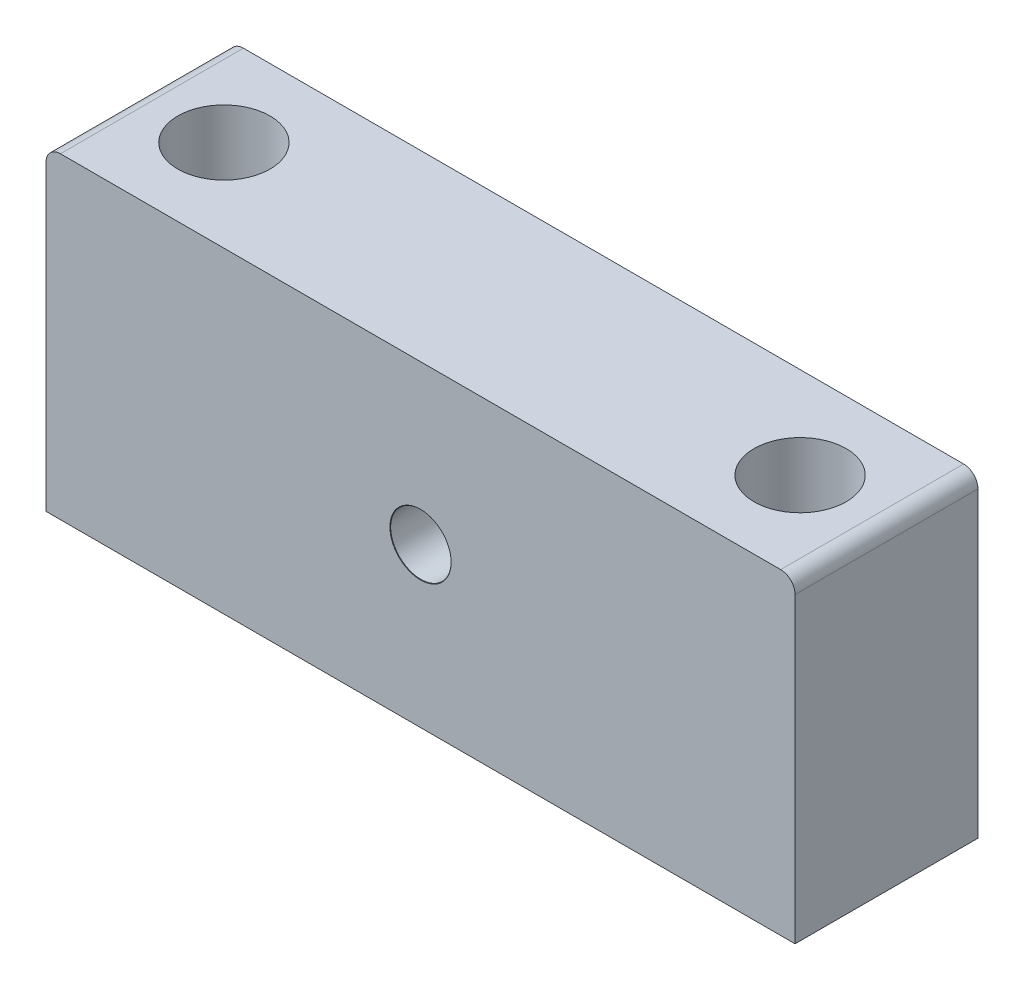
SolidWorks part; units mm, degrees
material "6061 Alloy"
ref_plane "Front Plane" through (0, 0, 0) normal (0, 0, 1) x (1, 0, 0)
ref_plane "Top Plane" through (0, 0, 0) normal (0, 1, 0) x (1, 0, 0)
ref_plane "Right Plane" through (0, 0, 0) normal (1, 0, 0) x (0, 0, -1)
sketch "Sketch1" plane through (0, 0, 0) normal (0, 0, 1) x (1, 0, 0)
  line L0 (-26, 0) -> (26, 0)
  line L1 (26, 0) -> (26, 6)
  line L2 (26, 6) -> (11, 6) construction
  line L3 (-26, 0) -> (-26, 6)
  line L4 (-26, 6) -> (-11, 6) construction
  line L5 (7.5, 22) -> (-7.5, 22)
  line L6 (-26, 6) -> (-26, 22)
  line L7 (-26, 22) -> (-7.5, 22)
  line L8 (7.5, 22) -> (26, 22)
  line L9 (26, 22) -> (26, 6)
  arc A0 (-11, 6) -> (-7.5, 22) centre (-3.6435, 12.7736) cw construction
  arc A1 (11, 6) -> (7.5, 22) centre (3.6435, 12.7736) ccw construction
  circle A2 centre (0, 11) radius 3 construction
  point P12 (0, 0)
  point P13 (0, 22)
  dimension "D6" = 10
  dimension "D8" = 6
  dimension "D1" = 6
  dimension "D2" = 52
  dimension "D3" = 15
  dimension "D4" = 15
  dimension "D5" = 22
  dimension "D7" = 11
extrude "Boss-Extrude1" add sketch "Sketch1" against normal blind 12.7 contours L5 L7 L6 L3 L0 L1 L9 L8
hole_wizard "Tap Drill for M5x0.8 Tap1" positions "3DSketch1" profile "Sketch2" hole size "M5x0.8" standard "ANSI Metric" end condition through all
sketch3d "3DSketch1"
  point P0 (0, 11, 0)
sketch "Sketch2" plane through (0, 11, 0) normal (1, 0, 0) x (0, -1, 0)
  line L0 (0, 0) -> (0, 12.7)
  line L1 (0, 12.7) -> (2.1, 12.7)
  line L2 (2.1, 12.7) -> (2.1, 0.025)
  line L3 (2.1, 0.025) -> (2.125, 0)
  line L5 (2.125, 0) -> (0, 0)
  line L6 (-2.1, 0.025) -> (-2.125, 0) construction
  line L11 (0, -6.35) -> (0, 107.95) construction
  dimension "Thru Hole Dia." = 4.2
  dimension "Thru Hole Depth" = 12.7
  dimension "Near C'Sink Dia." = 4.25
  dimension "Near C'Sink Angle" = 90
sketch "Sketch3" plane through (0, 0, 0) normal (0, -1, 0) x (1, 0, 0)
  line L0 (0, 0) -> (0, -12.7) construction
  line L1 (-26, -12.7) -> (26, -12.7) construction
  circle A0 centre (-20, -6.35) radius 3 construction
  circle A1 centre (20, -6.35) radius 3 construction
  point P8 (0, -6.35)
  dimension "D1" = 6
  dimension "D2" = 40
hole_wizard "M6 Clearance Hole1" positions "3DSketch2" profile "Sketch4" hole size "M6" standard "ANSI Metric" end condition through all
sketch3d "3DSketch2"
  point P0 (-20, 0, -6.35)
  point P2 (20, 0, -6.35)
sketch "Sketch4" plane through (-20, 0, -6.35) normal (1, 0, 0) x (0, 0, -1)
  line L0 (0, 0) -> (0, 22)
  line L1 (0, 22) -> (3.2, 22)
  line L2 (3.2, 22) -> (3.2, 0.125)
  line L3 (3.2, 0.125) -> (3.325, 0)
  line L5 (3.325, 0) -> (0, 0)
  line L6 (-3.2, 0.125) -> (-3.325, 0) construction
  line L11 (0, -6.35) -> (0, 107.95) construction
  dimension "Thru Hole Dia." = 6.4
  dimension "Thru Hole Depth" = 22
  dimension "Near C'Sink Dia." = 6.65
  dimension "Near C'Sink Angle" = 90
fillet "Fillet1" radius 1 2 edges at (26, 22, -6.35) (-26, 22, -6.35)
